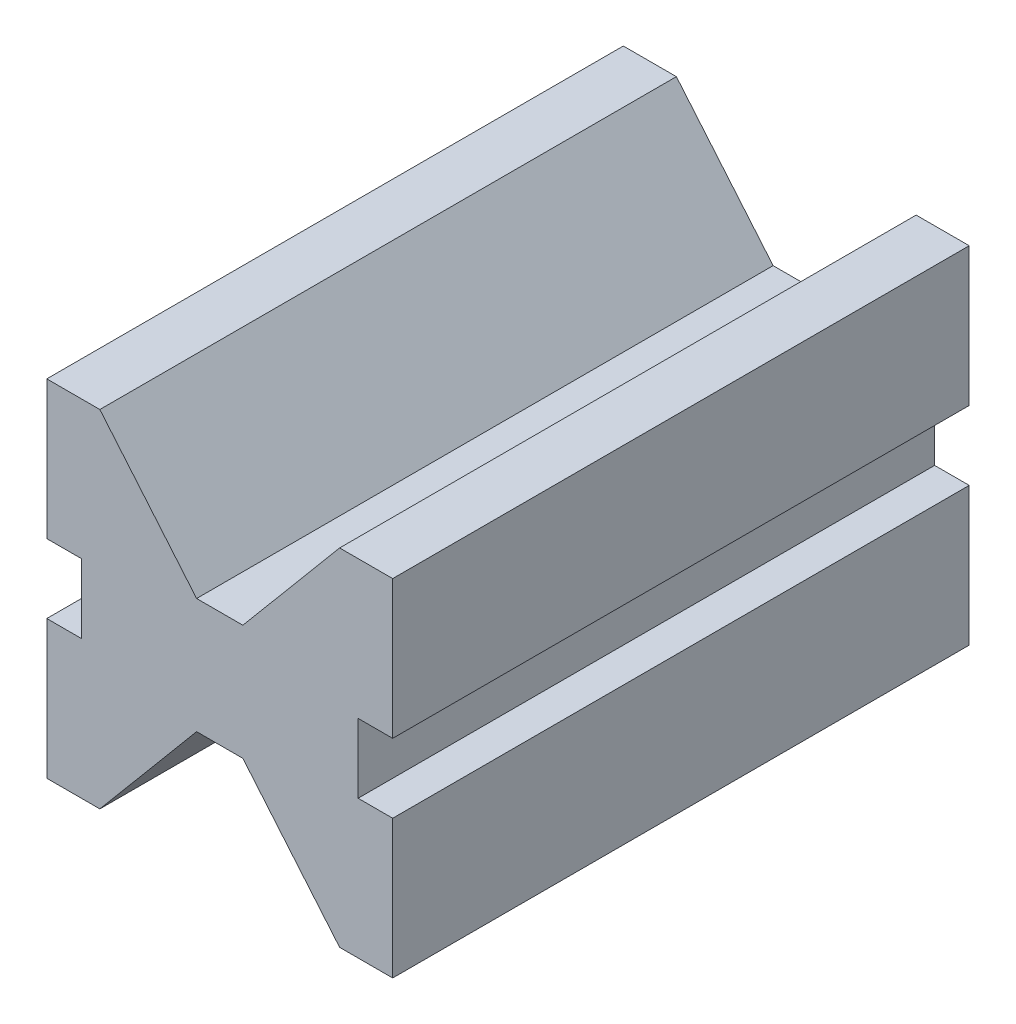
SolidWorks part; units mm, degrees
material "1060 Alloy"
ref_plane "Front Plane" through (0, 0, 0) normal (0, 0, 1) x (1, 0, 0)
ref_plane "Top Plane" through (0, 0, 0) normal (0, 1, 0) x (1, 0, 0)
ref_plane "Right Plane" through (0, 0, 0) normal (1, 0, 0) x (0, 0, -1)
sketch "Sketch2" plane through (0, 0, 0) normal (0, 0, 1) x (1, 0, 0)
  line L0 (-30, 6) -> (-24, 6)
  line L1 (-30, -30) -> (30, -30)
  line L2 (-30, -30) -> (-30, -6)
  line L3 (-30, 30) -> (30, 30)
  line L5 (-30, -30) -> (0, 0) construction
  line L6 (-30, 30) -> (0, 0) construction
  line L7 (-24, 6) -> (-24, -6)
  line L8 (-24, -6) -> (-30, -6)
  line L9 (-20.7947, -30) -> (-4.0127, -10)
  line L10 (-4.0127, -10) -> (4.0127, -10)
  line L11 (0, 30) -> (0, -30)
  line L12 (0, 30) -> (0, -30) construction
  line L13 (-30, 6) -> (-30, 30)
  line L14 (-20.7947, 30) -> (-4.0127, 10)
  line L15 (-4.0127, 10) -> (4.0127, 10)
  line L16 (30, 30) -> (0, 0) construction
  line L17 (30, -30) -> (0, 0) construction
  line L18 (20.7947, 30) -> (4.0127, 10)
  line L19 (30, 6) -> (30, 30)
  line L20 (20.7947, -30) -> (4.0127, -10)
  line L21 (24, -6) -> (30, -6)
  line L22 (24, 6) -> (24, -6)
  line L23 (30, -30) -> (30, -6)
  line L24 (30, 6) -> (24, 6)
  point P0 (0, 0)
  point P20 (0, 10)
  point P23 (0, -10)
  dimension "D1" = 60
  dimension "D2" = 20
  dimension "D3" = 24
  dimension "D4" = 12
  dimension "D5" = 6
  dimension "D6" = 20
  dimension "D8" = 50
extrude "Boss-Extrude1" add sketch "Sketch2" along normal mid plane 100 contours L13 L0 L7 L8 L2 L1 L9 L10 L11 L3 | L24 L19 L3 L18 L15 L11 L10 L20 L1 L23 L21 L22
